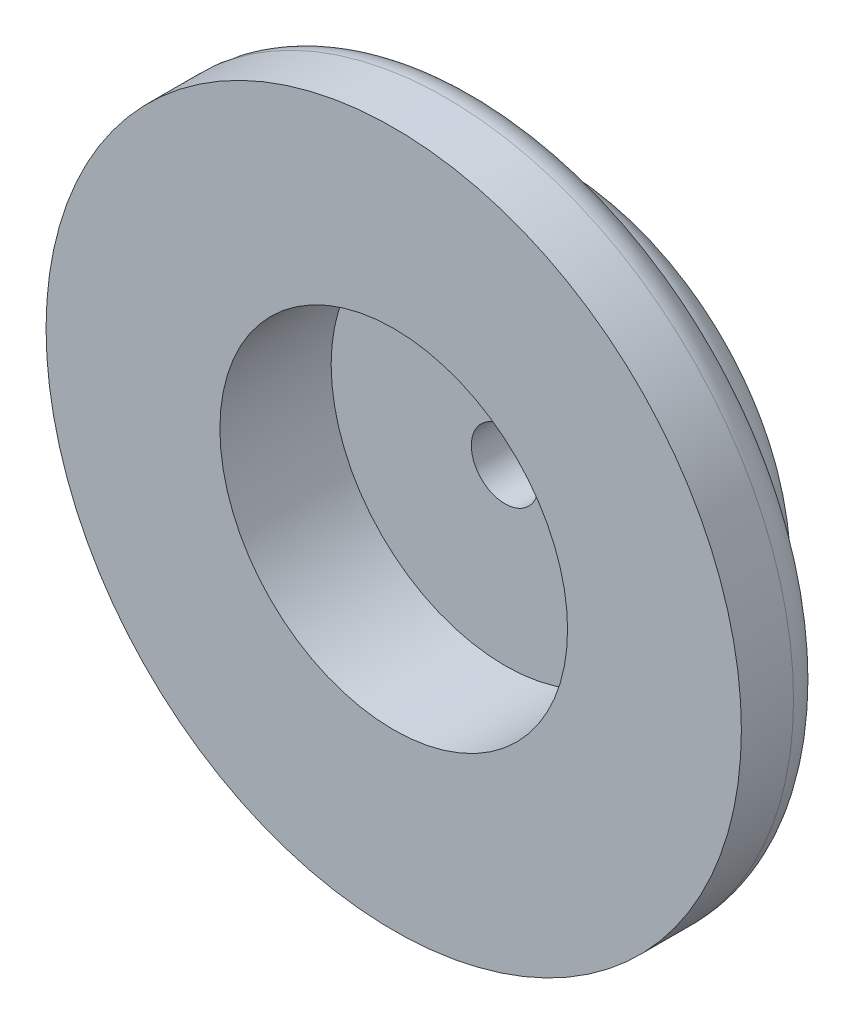
SolidWorks part; units mm, degrees
material "ABS"
ref_plane "Front Plane" through (0, 0, 0) normal (0, 0, 1) x (1, 0, 0)
ref_plane "Top Plane" through (0, 0, 0) normal (0, 1, 0) x (1, 0, 0)
ref_plane "Right Plane" through (0, 0, 0) normal (1, 0, 0) x (0, 0, -1)
sketch "Sketch1" plane through (0, 0, 0) normal (1, 0, 0) x (0, 0, -1)
  line L0 (0, 0) -> (79.248, 0) construction
  line L1 (79.248, 12.7) -> (79.248, 25.4)
  line L2 (79.248, 25.4) -> (85.598, 25.4)
  line L3 (79.248, 12.7) -> (87.376, 12.7)
  line L4 (87.376, 12.7) -> (87.376, 0)
  line L5 (91.948, 0) -> (91.948, 17.78)
  line L6 (91.948, 0) -> (87.376, 0)
  line L7 (85.598, 25.4) -> (85.598, 17.78)
  line L8 (91.948, 17.78) -> (85.598, 17.78)
  dimension "D1" = 12.7
  dimension "D2" = 12.7
  dimension "D3" = 12.7
  dimension "D4" = 17.78
  dimension "D5" = 4.572
revolve "Revolve1" add sketch "Sketch1" angle 360 about L0
fillet "Fillet1" radius 2.54 3 edges at (17.78, 0, -85.598) (17.78, 0, -91.948) (25.4, 0, -85.598)
hole_wizard "#10 (0.1935) Diameter Hole1" positions "Sketch3" profile "Sketch2" hole size "#10" standard "Ansi Inch"
sketch "Sketch3" plane through (0, 0, -91.948) normal (0, 0, -1) x (-1, 0, 0)
  line L0 (15.24, 0) -> (-15.24, 0) construction
  line L1 (0, -15.24) -> (0, 15.24) construction
  circle A0 centre (0, 0) radius 15.24 construction
  point P0 (0, 0)
sketch "Sketch2" plane through (0, 0, -91.948) normal (1, 0, 0) x (0, 1, 0)
  line L0 (0, 0) -> (0, 11.6366)
  line L1 (0, 11.6366) -> (2.4574, 10.16)
  line L2 (2.4574, 10.16) -> (2.4574, 0)
  line L5 (2.4574, 0) -> (0, 0)
  line L10 (0, 11.6366) -> (-2.4574, 10.16) construction
  line L11 (0, -6.35) -> (0, 107.95) construction
  dimension "Hole Dia." = 4.9149
  dimension "Hole Depth" = 10.16
  dimension "Drill Angle" = 118
